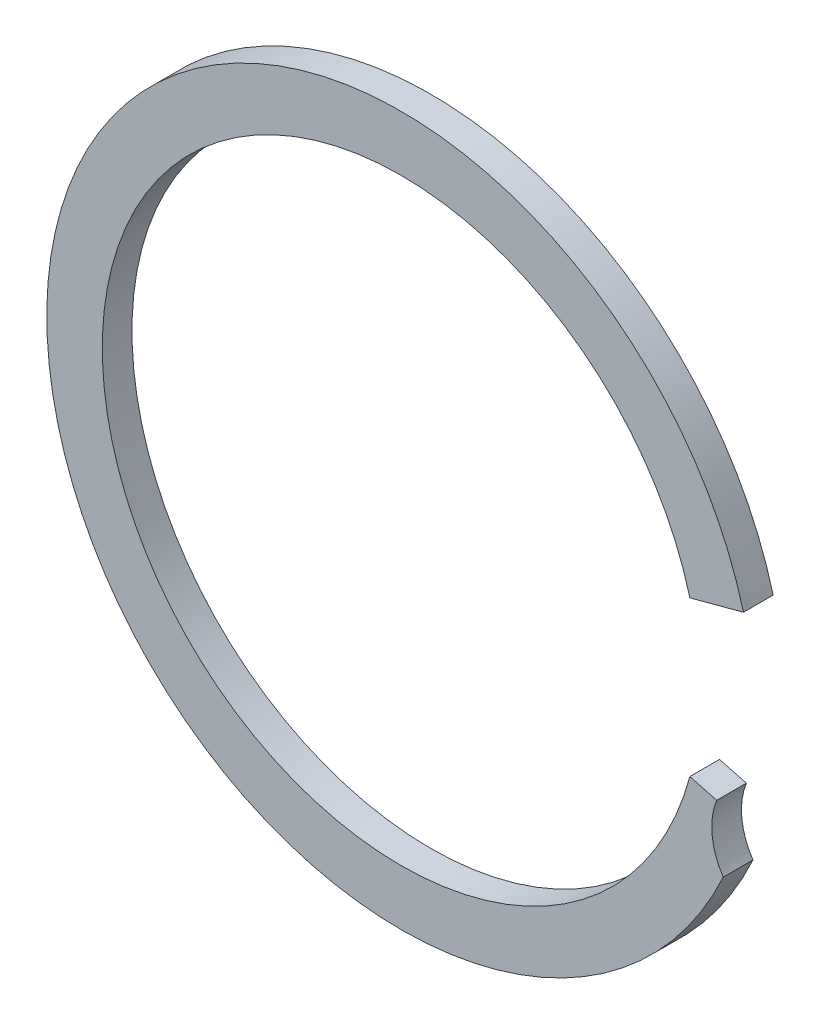
SolidWorks part; units mm, degrees
ref_plane "Front" through (0, 0, 0) normal (0, 0, 1) x (1, 0, 0)
ref_plane "Top" through (0, 0, 0) normal (0, 1, 0) x (1, 0, 0)
ref_plane "Right" through (0, 0, 0) normal (1, 0, 0) x (0, 0, -1)
sketch "Layout" plane through (0, 0, 0) normal (0, 0, 1) x (1, 0, 0)
  line L0 (-13.73, 0) -> (13.73, 0) construction
  line L1 (11.1854, -2.9971) -> (0, 0) construction
  line L2 (11.1854, 2.9971) -> (12.2238, 3.2754) construction
  line L3 (0, 0) -> (0, 3.4325) construction
  line L4 (0, 3.4325) -> (0, 6.865) construction
  line L5 (0, 6.865) -> (0, 10.2975) construction
  line L6 (0, 10.2975) -> (0, 13.73) construction
  line L7 (11.1854, 2.9971) -> (0, 0) construction
  line L9 (-13.73, 0) -> (-13.73, 1.15) construction
  line L10 (12.2238, 3.2754) -> (13.2622, 3.5536) construction
  line L11 (11.1854, -2.9971) -> (12.2238, -3.2754) construction
  line L12 (12.2238, -3.2754) -> (13.2622, -3.5536) construction
  line L13 (0, 10.2975) -> (21.0371, 10.2975) construction
  circle A0 centre (0, 0) radius 11.58 construction
  circle A1 centre (0, 0) radius 13.73 construction
  circle A2 centre (9.4157, 0) radius 4.3143 construction
  circle A3 centre (21.0371, 0) radius 10.2975 construction
  dimension "D1" = 15
  dimension "Ring OD" = 27.46
  dimension "Cad M" = 2.15
  dimension "thickness" = 1.15
sketch "Sketch2" plane through (0, 0, 0) normal (0, 0, 1) x (1, 0, 0)
  line L0 (-13.73, 0) -> (13.73, 0) construction
  line L1 (-13.73, 0) -> (13.73, 0) construction
  line L3 (11.1854, 2.9971) -> (12.2238, 3.2754) construction
  line L4 (12.2238, 3.2754) -> (13.2622, 3.5536) construction
  line L5 (11.1854, -2.9971) -> (0, 0) construction
  line L6 (11.1854, -2.9971) -> (0, 0) construction
  line L8 (12.2238, -3.2754) -> (13.2622, -3.5536) construction
  line L9 (11.1854, 2.9971) -> (12.2238, 3.2754)
  line L10 (12.2238, 3.2754) -> (13.2622, 3.5536)
  line L11 (11.1854, -2.9971) -> (12.2238, -3.2754)
  circle A0 centre (0, 0) radius 13.73 construction
  circle A3 centre (0, 0) radius 11.58 construction
  circle A4 centre (21.0371, 0) radius 10.2975 construction
  arc A5 (13.2622, 3.5536) -> (12.4788, -5.7265) centre (0, 0) ccw
  arc A6 (11.1854, 2.9971) -> (11.1854, -2.9971) centre (0, 0) ccw
  arc A7 (12.2238, -3.2754) -> (12.4788, -5.7265) centre (14.6711, -4.2596) ccw
extrude "Boss-Extrude1" add sketch "Sketch2" along normal blind 1.15
sketch "Sketch3" plane through (0, 0, 0) normal (0, 0, 1) x (1, 0, 0)
  line L0 (0, 0) -> (13.2622, 0) construction
  line L1 (8.1883, -8.1883) -> (9.7086, -9.7086) construction
  arc A0 (11.1854, 2.9971) -> (11.1854, -2.9971) centre (0, 0) ccw construction
  arc A1 (13.2622, 3.5536) -> (12.4788, -5.7265) centre (0, 0) ccw construction
  dimension "D1" = 45
sketch "Sketch4" plane through (0, 0, 0) normal (0, 0, 1) x (1, 0, 0)
  circle A0 centre (0, 0) radius 13.73 construction
  arc A1 (13.2622, 3.5536) -> (12.4788, -5.7265) centre (0, 0) ccw construction
equation "\"D1@Boss-Extrude1\"=\"thickness@Layout\""
